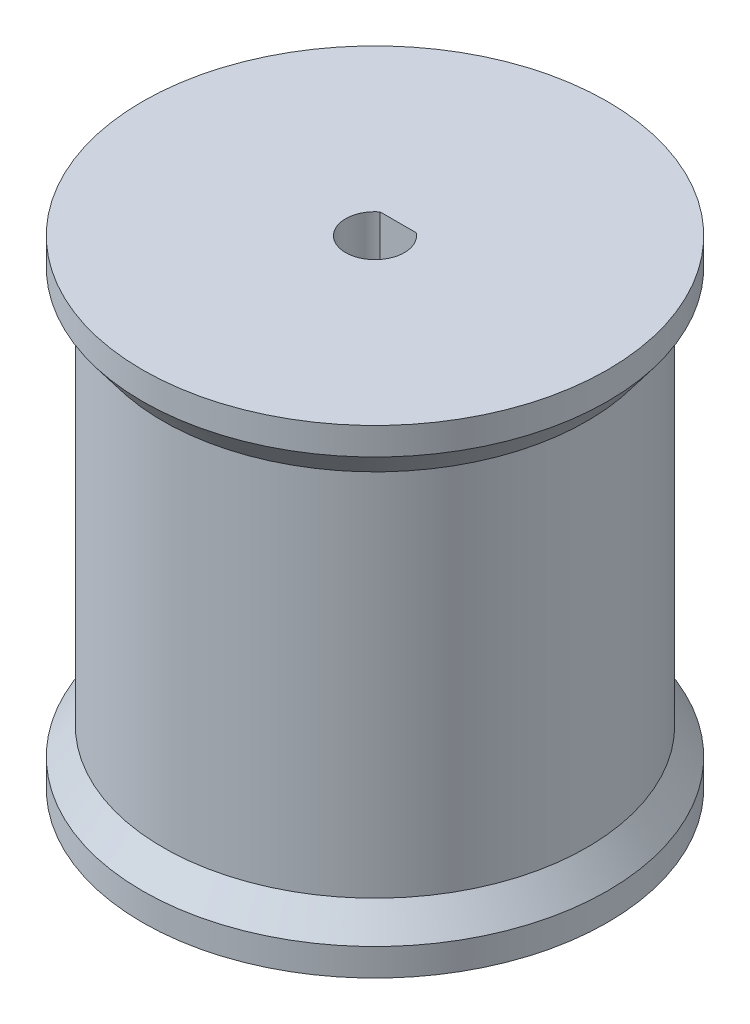
SolidWorks part; units mm, degrees
ref_plane "Front Plane" through (0, 0, 0) normal (0, 0, 1) x (1, 0, 0)
ref_plane "Top Plane" through (0, 0, 0) normal (0, 1, 0) x (1, 0, 0)
ref_plane "Right Plane" through (0, 0, 0) normal (1, 0, 0) x (0, 0, -1)
sketch "Sketch1" plane through (0, 0, 0) normal (0, 0, 1) x (1, 0, 0)
  line L0 (0, 0) -> (0, 35)
  line L1 (0, 35) -> (-17, 35)
  line L2 (-17, 35) -> (-17, 33)
  line L3 (-17, 33) -> (-15.5, 31)
  line L4 (-15.5, 31) -> (-15.5, 4)
  line L5 (-15.5, 4) -> (-17, 2)
  line L6 (-17, 2) -> (-17, 0)
  line L7 (-17, 0) -> (0, 0)
  dimension "D1" = 35
  dimension "D2" = 2
  dimension "D3" = 2
  dimension "D4" = 2
  dimension "D5" = 2
  dimension "D6" = 1.5
  dimension "D7" = 1.5
  dimension "D8" = 17
  dimension "D9" = 17
revolve "Revolve1" add sketch "Sketch1" angle 360 about L0
sketch "Sketch2" plane through (0, 35, 0) normal (0, 1, 0) x (1, 0, 0)
  line L0 (-1.325, 1.6932) -> (1.325, 1.6932)
  arc A0 (-1.325, 1.6932) -> (1.325, 1.6932) centre (0, 0) ccw
  dimension "D1" = 4.3
  dimension "D2" = 2.65
extrude "Cut-Extrude1" cut sketch "Sketch2" against normal blind 8.2
